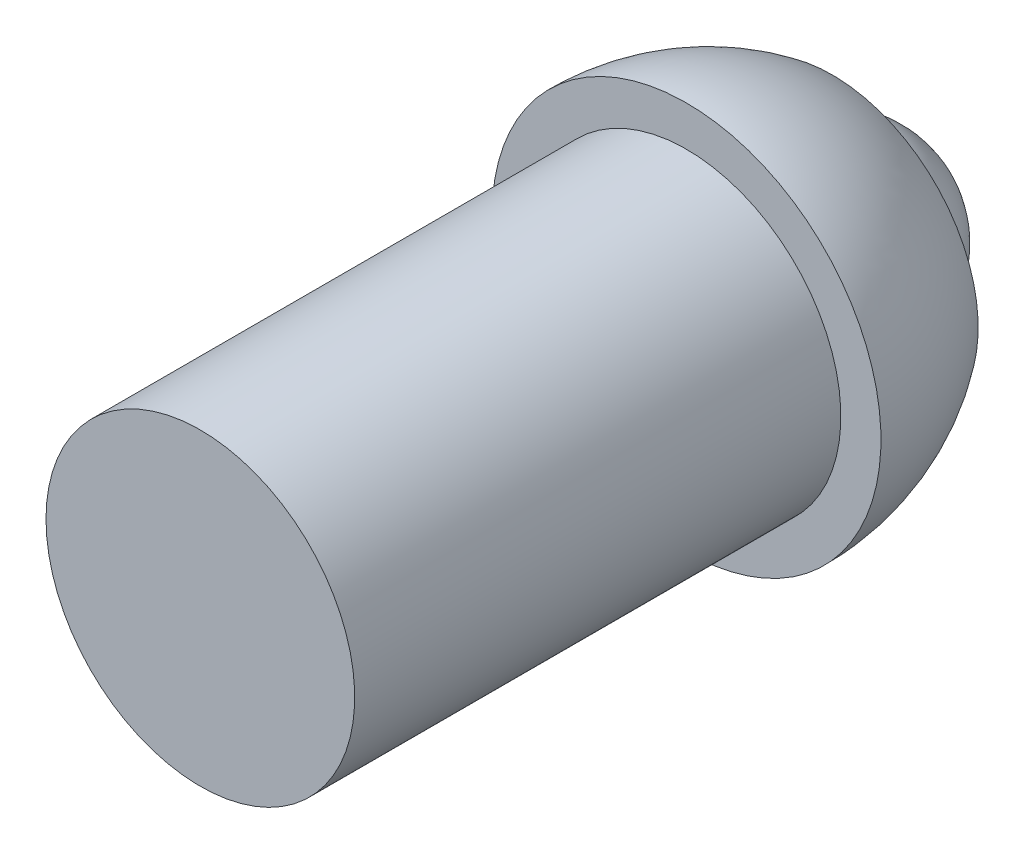
SolidWorks part; units mm, degrees
material "ABS"
ref_plane "Ground_Plane" through (0, 0, 0) normal (0, 0, 1) x (1, 0, 0)
ref_plane "VehicleCentre_Plane" through (0, 0, 0) normal (0, 1, 0) x (1, 0, 0)
ref_plane "FrontAxle_Plane" through (0, 0, 0) normal (1, 0, 0) x (0, 0, -1)
sketch "Sketch1" plane through (0, 0, 0) normal (0, 1, 0) x (1, 0, 0)
  line L0 (0, -10) -> (3.175, -10)
  line L1 (3.175, -10) -> (3.175, 0)
  line L2 (3.175, 0) -> (4, 0)
  line L3 (3, 3) -> (2, 3)
  line L4 (0, 5) -> (0, -10)
  arc A0 (4, 0) -> (3, 3) centre (-1, 0) ccw
  arc A1 (2, 3) -> (0, 5) centre (0, 3) ccw
  dimension "D4" = 5
  dimension "D5" = 2
  dimension "D6" = 2
  dimension "D1" = 3.175
  dimension "D2" = 4
  dimension "D3" = 3
  dimension "D7" = 10
revolve "Revolve1" add sketch "Sketch1" angle 360 about L4
